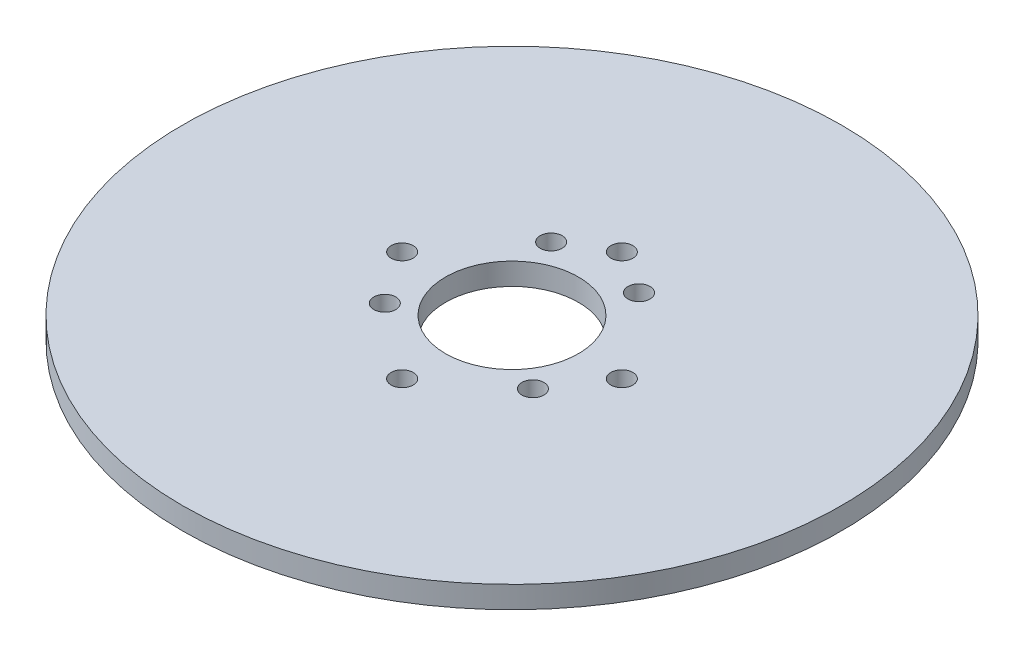
SolidWorks part; units mm, degrees
ref_plane "Front Plane" through (0, 0, 0) normal (0, 0, 1) x (1, 0, 0)
ref_plane "Top Plane" through (0, 0, 0) normal (0, 1, 0) x (1, 0, 0)
ref_plane "Right Plane" through (0, 0, 0) normal (1, 0, 0) x (0, 0, -1)
sketch "Sketch1" plane through (0, 0, 0) normal (0, 1, 0) x (1, 0, 0)
  line L0 (-20, 40.3113) -> (-33.7, -21.6932) construction
  line L1 (20, 40.3113) -> (33.7, -21.6932) construction
  line L2 (-20, 40.3113) -> (33.7, -21.6932) construction
  line L3 (20, 40.3113) -> (-33.7, -21.6932) construction
  line L4 (-20, 40.3113) -> (20, 40.3113) construction
  line L5 (-20, 40.3113) -> (0, 0) construction
  circle A0 centre (-20, 40.3113) radius 5
  circle A1 centre (20, 40.3113) radius 5
  circle A3 centre (33.7, -21.6932) radius 5
  circle A4 centre (-33.7, -21.6932) radius 5
  arc A10 (22.9505, 23.6727) -> (23.6461, 23.8093) centre (20.4099, 38.456) ccw
  circle A11 centre (0, 2.5) radius 30.25
  circle A12 centre (0, 52.5) radius 5
  circle A13 centre (50, 2.5) radius 5
  circle A14 centre (0, -47.5) radius 5
  circle A15 centre (-50, 2.5) radius 5
  circle A16 centre (0, 2.5) radius 150
  point P2 (0, 40.3113)
  point P17 (-33.7, -21.6932)
  point P18 (0, 0)
  point P25 (0, 2.5)
  point P26 (0, 0)
  dimension "D4" = 10
  dimension "D1" = 63.5
  dimension "D6" = 2.5
  dimension "D7" = 50
  dimension "D8" = 10
  dimension "D9" = 4
  dimension "D10" = 300
  dimension "D11" = 60.5
  dimension "D2" = 40
  dimension "D5" = 67.4
extrude "Boss-Extrude1" add sketch "Sketch1" along normal blind 10
